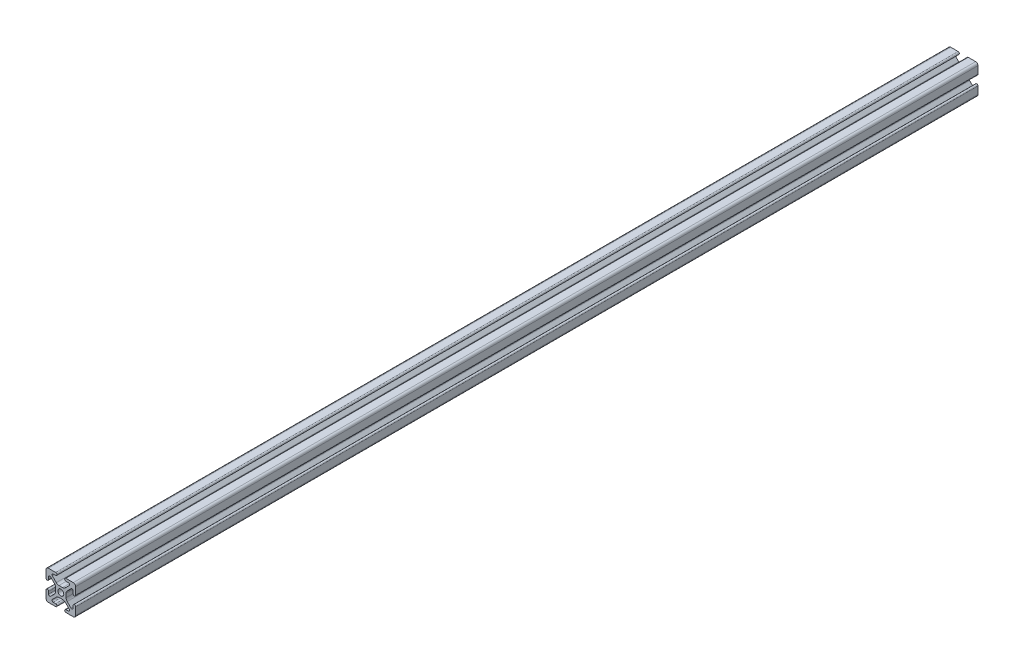
SolidWorks part; units mm, degrees
material "6061 Alloy"
ref_plane "Front Plane" through (0, 0, 0) normal (0, 0, 1) x (1, 0, 0)
ref_plane "Top Plane" through (0, 0, 0) normal (0, 1, 0) x (1, 0, 0)
ref_plane "Right Plane" through (0, 0, 0) normal (1, 0, 0) x (0, 0, -1)
sketch "Sketch1" plane through (0, 0, 0) normal (0, 0, 1) x (1, 0, 0)
  line L0 (-8.6363, 7.1116) -> (-5.4322, 3.9121)
  line L1 (-4.455, 1.5554) -> (-4.455, -1.5554)
  line L2 (-5.4322, -3.9121) -> (-8.6363, -7.1116)
  line L3 (-10.36, -6.3969) -> (-10.36, -4.32)
  line L4 (-12.5, -4.32) -> (-12.5, -8.6518)
  line L5 (-12.5, -8.6518) -> (-12.5, -10.5371)
  line L6 (-10.5371, -12.5) -> (-8.4416, -12.5)
  line L7 (-8.4416, -12.5) -> (-4.3879, -12.5)
  line L8 (-4.3879, -10.36) -> (-6.42, -10.36)
  line L9 (-7.1337, -8.6353) -> (-3.7953, -5.3018)
  line L10 (-1.5554, -4.375) -> (1.5554, -4.375)
  line L11 (10.36, 4.32) -> (10.36, 6.3969)
  line L12 (12.5, 7.9913) -> (12.5, 4.32)
  line L13 (12.5, 10.5371) -> (12.5, 7.9913)
  line L14 (4.32, 12.5) -> (10.5371, 12.5)
  line L16 (6.42, 10.36) -> (4.32, 10.36)
  line L17 (3.7953, 5.3018) -> (7.1337, 8.6353)
  line L18 (7.1337, -8.6353) -> (3.7953, -5.3018)
  line L19 (4.3879, -10.36) -> (6.42, -10.36)
  line L20 (8.4416, -12.5) -> (4.3879, -12.5)
  line L21 (10.5371, -12.5) -> (8.4416, -12.5)
  line L22 (12.5, -8.6518) -> (12.5, -10.5371)
  line L23 (12.5, -4.32) -> (12.5, -8.6518)
  line L24 (10.36, -6.3969) -> (10.36, -4.32)
  line L25 (5.4322, -3.9121) -> (8.6363, -7.1116)
  line L26 (4.455, 1.5554) -> (4.455, -1.5554)
  line L27 (8.6363, 7.1116) -> (5.4322, 3.9121)
  line L28 (1.5554, 4.375) -> (-1.5554, 4.375)
  line L29 (-3.7953, 5.3018) -> (-7.1337, 8.6353)
  line L30 (-6.42, 10.36) -> (-4.32, 10.36)
  line L32 (-4.32, 12.5) -> (-10.5371, 12.5)
  line L33 (-12.5, 10.5371) -> (-12.5, 7.9913)
  line L34 (-12.5, 7.9913) -> (-12.5, 4.32)
  line L35 (-10.36, 4.32) -> (-10.36, 6.3969)
  line L36 (-15.7693, 0) -> (12.5, 0) construction
  line L37 (0, 13.9334) -> (0, -12.3541) construction
  circle A0 centre (0, 0) radius 2.5
  arc A1 (-8.6363, 7.1116) -> (-10.36, 6.3969) centre (-9.35, 6.3969) ccw
  arc A2 (-4.455, 1.5554) -> (-5.4322, 3.9121) centre (-7.7855, 1.5554) ccw
  arc A3 (-5.4322, -3.9121) -> (-4.455, -1.5554) centre (-7.7855, -1.5554) ccw
  arc A4 (-10.36, -6.3969) -> (-8.6363, -7.1116) centre (-9.35, -6.3969) ccw
  arc A5 (-10.36, -4.32) -> (-12.5, -4.32) centre (-11.43, -4.32) ccw
  arc A6 (-12.5, -10.5371) -> (-10.5371, -12.5) centre (-10.5371, -10.5371) ccw
  arc A7 (-4.3879, -12.5) -> (-4.3879, -10.36) centre (-4.3879, -11.43) ccw
  arc A8 (-7.1337, -8.6353) -> (-6.42, -10.36) centre (-6.42, -9.35) ccw
  arc A9 (-1.5554, -4.375) -> (-3.7953, -5.3018) centre (-1.5554, -7.545) ccw
  arc A10 (12.5, 4.32) -> (10.36, 4.32) centre (11.43, 4.32) cw
  arc A11 (10.5371, 12.5) -> (12.5, 10.5371) centre (10.5371, 10.5371) cw
  arc A12 (4.32, 10.36) -> (4.32, 12.5) centre (4.32, 11.43) cw
  arc A13 (6.42, 10.36) -> (7.1337, 8.6353) centre (6.42, 9.35) cw
  arc A14 (3.7953, 5.3018) -> (1.5554, 4.375) centre (1.5554, 7.545) cw
  arc A15 (1.5554, -4.375) -> (3.7953, -5.3018) centre (1.5554, -7.545) cw
  arc A16 (7.1337, -8.6353) -> (6.42, -10.36) centre (6.42, -9.35) cw
  arc A17 (4.3879, -12.5) -> (4.3879, -10.36) centre (4.3879, -11.43) cw
  arc A18 (12.5, -10.5371) -> (10.5371, -12.5) centre (10.5371, -10.5371) cw
  arc A19 (10.36, -4.32) -> (12.5, -4.32) centre (11.43, -4.32) cw
  arc A20 (10.36, -6.3969) -> (8.6363, -7.1116) centre (9.35, -6.3969) cw
  arc A21 (5.4322, -3.9121) -> (4.455, -1.5554) centre (7.7855, -1.5554) cw
  arc A22 (4.455, 1.5554) -> (5.4322, 3.9121) centre (7.7855, 1.5554) cw
  arc A23 (8.6363, 7.1116) -> (10.36, 6.3969) centre (9.35, 6.3969) cw
  arc A24 (-3.7953, 5.3018) -> (-1.5554, 4.375) centre (-1.5554, 7.545) ccw
  arc A25 (-6.42, 10.36) -> (-7.1337, 8.6353) centre (-6.42, 9.35) ccw
  arc A26 (-4.32, 10.36) -> (-4.32, 12.5) centre (-4.32, 11.43) ccw
  arc A27 (-10.5371, 12.5) -> (-12.5, 10.5371) centre (-10.5371, 10.5371) ccw
  arc A28 (-12.5, 4.32) -> (-10.36, 4.32) centre (-11.43, 4.32) ccw
  dimension "D4" = 14.86
  dimension "D5" = 2.14
  dimension "D6" = 6.5
  dimension "D7" = 8.75
  dimension "D8" = 1.01
  dimension "D9" = 3.17
  dimension "D14" = 5
  dimension "D1" = 25
  dimension "D2" = 8.91
  dimension "D3" = 12.5
  dimension "D12" = 2.14
extrude "Extrude1" add sketch "Sketch1" against normal blind 762
